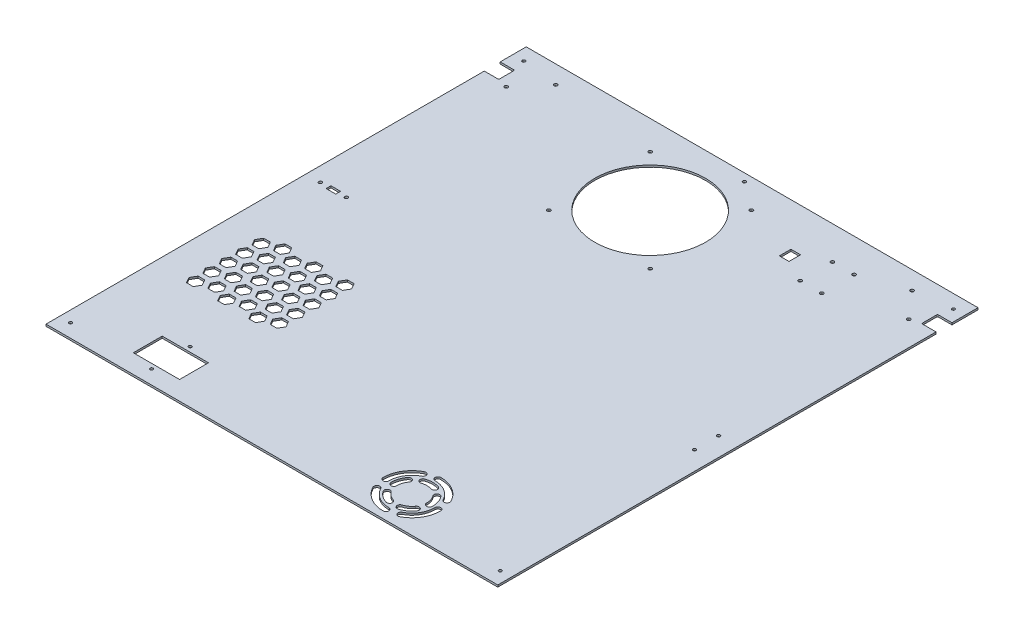
SolidWorks part; units mm, degrees
ref_plane "Alzado" through (0, 0, 0) normal (0, 0, 1) x (1, 0, 0)
ref_plane "Planta" through (0, 0, 0) normal (0, 1, 0) x (1, 0, 0)
ref_plane "Vista lateral" through (0, 0, 0) normal (1, 0, 0) x (0, 0, -1)
sketch "Croquis1" plane through (0, 0, 0) normal (0, 1, 0) x (1, 0, 0)
  line L1 (0, 0) -> (470.5, 0)
  line L2 (0, 0) -> (0, 420)
  line L3 (0, 420) -> (470.5, 420)
  line L4 (470.5, 0) -> (470.5, 420)
  dimension "D1" = 420
  dimension "D2" = 470.5
extrude "Saliente-Extruir1" add sketch "Croquis1" along normal blind 2
sketch "Croquis2" plane through (0, 2, 0) normal (0, 1, 0) x (1, 0, 0)
  line L0 (470.5, 420) -> (0, 420) construction
  line L1 (0, 420) -> (0, 0) construction
  line L2 (235.25, 420) -> (235.25, 0) construction
  line L3 (0, 0) -> (470.5, 0) construction
  line L4 (0, 210) -> (470.5, 210) construction
  line L5 (470.5, 0) -> (470.5, 420) construction
  circle A0 centre (12.5, 405) radius 1.55
  circle A1 centre (458, 405) radius 1.55
  circle A2 centre (458, 15) radius 1.55
  circle A3 centre (12.5, 15) radius 1.55
  dimension "D1" = 3.1
  dimension "D2" = 15
  dimension "D3" = 12.5
extrude "Cortar-Extruir1" cut sketch "Croquis2" against normal up to surface (2 mm away) up to face at (235.25, 0, -210)
sketch "Croquis3" plane through (0, 2, 0) normal (0, 1, 0) x (1, 0, 0)
  line L0 (470, 419.5) -> (0.5, 419.5)
  line L1 (0.5, 419.5) -> (0.5, 0.5)
  line L2 (0.5, 0.5) -> (470, 0.5)
  line L3 (470, 0.5) -> (470, 419.5)
  line L4 (0, 420) -> (0, 0)
  line L5 (0, 0) -> (470.5, 0)
  line L6 (470.5, 0) -> (470.5, 420)
  line L7 (470.5, 420) -> (0, 420)
  line L8 (0, 420) -> (0, 0)
  line L9 (0, 0) -> (470.5, 0)
  line L10 (470.5, 0) -> (470.5, 420)
  line L11 (470.5, 420) -> (0, 420)
  dimension "D1" = 0
  dimension "D2" = 0.5
extrude "Cortar-Extruir2" cut sketch "Croquis3" against normal up to surface (2 mm away) up to face at (12.5, 0, -16.55)
sketch "Croquis4" plane through (0, 2, 0) normal (0, 1, 0) x (1, 0, 0)
  line L0 (0.5, 0.5) -> (470, 0.5) construction
  line L1 (0.5, 419.5) -> (0.5, 0.5) construction
  circle A0 centre (343.5, 38) radius 27 construction
  arc A1 (343.5, 65) -> (367.4419, 50.4815) centre (343.5, 38) cw construction
  arc A2 (370.1021, 51.8683) -> (343.5, 68) centre (343.5, 38) ccw
  arc A3 (364.7817, 49.0947) -> (343.5, 62) centre (343.5, 38) ccw
  arc A4 (364.7817, 49.0947) -> (370.1021, 51.8683) centre (367.4419, 50.4815) ccw
  arc A5 (343.5, 68) -> (343.5, 62) centre (343.5, 65) ccw
  arc A6 (354.5947, 16.7183) -> (367.5, 38) centre (343.5, 38) ccw
  arc A7 (354.5947, 16.7183) -> (357.3683, 11.3979) centre (355.9815, 14.0581) ccw
  arc A8 (373.5, 38) -> (367.5, 38) centre (370.5, 38) ccw
  arc A9 (357.3683, 11.3979) -> (373.5, 38) centre (343.5, 38) ccw
  arc A10 (370.5, 38) -> (355.9815, 14.0581) centre (343.5, 38) cw construction
  arc A11 (322.2183, 26.9053) -> (343.5, 14) centre (343.5, 38) ccw
  arc A12 (322.2183, 26.9053) -> (316.8979, 24.1317) centre (319.5581, 25.5185) ccw
  arc A13 (343.5, 8) -> (343.5, 14) centre (343.5, 11) ccw
  arc A14 (316.8979, 24.1317) -> (343.5, 8) centre (343.5, 38) ccw
  arc A15 (343.5, 11) -> (319.5581, 25.5185) centre (343.5, 38) cw construction
  arc A16 (332.4053, 59.2817) -> (319.5, 38) centre (343.5, 38) ccw
  arc A17 (332.4053, 59.2817) -> (329.6317, 64.6021) centre (331.0185, 61.9419) ccw
  arc A18 (313.5, 38) -> (319.5, 38) centre (316.5, 38) ccw
  arc A19 (329.6317, 64.6021) -> (313.5, 38) centre (343.5, 38) ccw
  arc A20 (316.5, 38) -> (331.0185, 61.9419) centre (343.5, 38) cw construction
  circle A21 centre (343.5, 38) radius 18.5 construction
  arc A22 (337.5, 55.5) -> (349.5, 55.5) centre (343.5, 38) cw construction
  arc A23 (350.473, 58.3378) -> (336.527, 58.3378) centre (343.5, 38) ccw
  arc A24 (348.527, 52.6622) -> (338.473, 52.6622) centre (343.5, 38) ccw
  arc A25 (348.527, 52.6622) -> (350.473, 58.3378) centre (349.5, 55.5) ccw
  arc A26 (336.527, 58.3378) -> (338.473, 52.6622) centre (337.5, 55.5) ccw
  arc A27 (358.2894, 49.1141) -> (361.9976, 37.7015) centre (343.5, 38) cw construction
  arc A28 (364.9972, 37.653) -> (360.6877, 50.9164) centre (343.5, 38) ccw
  arc A29 (358.998, 37.7499) -> (355.8911, 47.3118) centre (343.5, 38) ccw
  arc A30 (358.998, 37.7499) -> (364.9972, 37.653) centre (361.9976, 37.7015) ccw
  arc A31 (360.6877, 50.9164) -> (355.8911, 47.3118) centre (358.2894, 49.1141) ccw
  arc A32 (358.6403, 27.3689) -> (348.9321, 20.3155) centre (343.5, 38) cw construction
  arc A33 (349.813, 17.4477) -> (361.0955, 25.645) centre (343.5, 38) ccw
  arc A34 (348.0513, 23.1832) -> (356.1852, 29.0929) centre (343.5, 38) ccw
  arc A35 (348.0513, 23.1832) -> (349.813, 17.4477) centre (348.9321, 20.3155) ccw
  arc A36 (361.0955, 25.645) -> (356.1852, 29.0929) centre (358.6403, 27.3689) ccw
  arc A37 (338.0679, 20.3155) -> (328.3597, 27.3689) centre (343.5, 38) cw construction
  arc A38 (325.9045, 25.645) -> (337.187, 17.4477) centre (343.5, 38) ccw
  arc A39 (330.8148, 29.0929) -> (338.9487, 23.1832) centre (343.5, 38) ccw
  arc A40 (330.8148, 29.0929) -> (325.9045, 25.645) centre (328.3597, 27.3689) ccw
  arc A41 (337.187, 17.4477) -> (338.9487, 23.1832) centre (338.0679, 20.3155) ccw
  arc A42 (325.0024, 37.7015) -> (328.7106, 49.1141) centre (343.5, 38) cw construction
  arc A43 (326.3123, 50.9164) -> (322.0028, 37.653) centre (343.5, 38) ccw
  arc A44 (331.1089, 47.3118) -> (328.002, 37.7499) centre (343.5, 38) ccw
  arc A45 (331.1089, 47.3118) -> (326.3123, 50.9164) centre (328.7106, 49.1141) ccw
  arc A46 (322.0028, 37.653) -> (328.002, 37.7499) centre (325.0024, 37.7015) ccw
  circle A94 centre (458, 405) radius 1.55 construction
  point P9 (357.5, 61.0868)
  point P19 (366.5868, 24)
  point P26 (329.5, 14.9132)
  point P33 (320.4132, 52)
  point P38 (343.5, 38)
  point P40 (343.5, 56.5)
  point P48 (361.0945, 43.7168)
  point P57 (354.374, 23.0332)
  point P64 (332.626, 23.0332)
  point P71 (325.9055, 43.7168)
  point P76 (343.5, 38)
  point P125 (302, 221.5)
  point P183 (302, 221.5)
  dimension "D1" = 54
  dimension "D7" = 37
  dimension "D2" = 37.5
  dimension "D3" = 343
  dimension "D4" = 28
  dimension "D5" = 6
  dimension "D8" = 12
  dimension "D9" = 6
  dimension "D6" = 4
  dimension "D10" = 5
extrude "Cortar-Extruir3" cut sketch "Croquis4" against normal up to surface (2 mm away) up to face at (12.5, 0, -406.55)
sketch "Croquis5" plane through (0, 0, 0) normal (0, -1, 0) x (1, 0, 0)
  line L0 (120, -35.5) -> (72, -35.5) construction
  line L1 (120, -50.5) -> (72, -50.5)
  line L2 (120, -50.5) -> (120, -20.5)
  line L3 (120, -20.5) -> (72, -20.5)
  line L4 (72, -50.5) -> (72, -20.5)
  line L5 (470, -0.5) -> (470, -419.5) construction
  line L6 (0.5, -0.5) -> (470, -0.5) construction
  circle A1 centre (96, -15.5) radius 1.55
  circle A2 centre (96, -55.5) radius 1.55
  dimension "D3" = 3.1
  dimension "D1" = 48
  dimension "D2" = 30
  dimension "D4" = 5
  dimension "D5" = 24
  dimension "D6" = 350
  dimension "D7" = 20
extrude "Cortar-Extruir4" cut sketch "Croquis5" against normal up to surface (2 mm away) up to face at (343.5, 2, -55.5135)
sketch "Croquis8" plane through (0, 0, 0) normal (0, -1, 0) x (1, 0, 0)
  line L1 (470, -419.5) -> (0.5, -419.5)
  line L2 (470, -419.5) -> (470, -449.5)
  line L3 (470, -449.5) -> (0.5, -449.5)
  line L4 (0.5, -419.5) -> (0.5, -449.5)
  dimension "D1" = 30
extrude "Saliente-Extruir2" add sketch "Croquis8" against normal up to surface (2 mm away) up to face at (96, 2, -57.05)
sketch "Croquis10" plane through (0, 0, 0) normal (0, -1, 0) x (1, 0, 0)
  circle A0 centre (458, -405) radius 1.75
  circle A1 centre (12.5, -405) radius 1.75
  dimension "D1" = 3.5
  dimension "D2" = 3.5
extrude "Saliente-Extruir3" add sketch "Croquis10" against normal up to surface (2 mm away) up to face at (96, 2, -57.05)
sketch "Croquis11" plane through (0, 0, -449.5) normal (0, 0, -1) x (-1, 0, 0)
  line L4 (-0.5, 2) -> (-470, 2)
  line L5 (-470, 2) -> (-470, 0)
  line L6 (-470, 0) -> (-0.5, 0)
  line L7 (-0.5, 0) -> (-0.5, 2)
  line L8 (-0.5, 2) -> (-470, 2)
  line L9 (-470, 2) -> (-470, 0)
  line L10 (-470, 0) -> (-0.5, 0)
  line L11 (-0.5, 0) -> (-0.5, 2)
  dimension "D1" = 0
extrude "Saliente-Extruir4" add sketch "Croquis11" along normal blind 50
sketch "Croquis12" plane through (0, 0, 0) normal (0, -1, 0) x (1, 0, 0)
  line L0 (470, -0.5) -> (470, -499.5) construction
  line L1 (0.5, -499.5) -> (0.5, -0.5) construction
  line L3 (470, -499.5) -> (0.5, -499.5) construction
  circle A0 centre (458, -485) radius 1.55
  circle A1 centre (12.5, -485) radius 1.55
  dimension "D1" = 3.1
  dimension "D2" = 3.1
  dimension "D3" = 12
  dimension "D4" = 12
  dimension "D5" = 14.5
  dimension "D6" = 14.5
extrude "Cortar-Extruir8" cut sketch "Croquis12" against normal up to surface (2 mm away) up to face at (96, 2, -57.05)
sketch "Croquis13" plane through (0, 0, 0) normal (0, -1, 0) x (1, 0, 0)
  line L0 (470, -0.5) -> (470, -499.5) construction
  line L1 (470, -499.5) -> (0.5, -499.5) construction
  line L3 (330, -454.5) -> (320, -454.5)
  line L4 (330, -454.5) -> (330, -442.5)
  line L5 (330, -442.5) -> (320, -442.5)
  line L6 (320, -454.5) -> (320, -442.5)
  circle A0 centre (353, -464.5) radius 1.75
  circle A1 centre (353, -431) radius 1.75
  circle A2 centre (375.5, -464.5) radius 1.75
  circle A3 centre (375.5, -431) radius 1.75
  dimension "D1" = 3.5
  dimension "D2" = 33.5
  dimension "D3" = 117
  dimension "D4" = 35
  dimension "D5" = 10
  dimension "D6" = 12
  dimension "D7" = 45
  dimension "D8" = 150
  dimension "D9" = 22.5
  dimension "D10" = 22.5
extrude "Cortar-Extruir9" cut sketch "Croquis13" against normal up to surface (2 mm away) up to face at (458, 2, -486.55)
sketch "Croquis15" plane through (0, 0, 0) normal (0, -1, 0) x (1, 0, 0)
  line L0 (470, -0.5) -> (470, -499.5) construction
  line L2 (470, -499.5) -> (0.5, -499.5) construction
  circle A0 centre (450, -249.5) radius 1.6
  circle A1 centre (450, -224.5) radius 1.6
  dimension "D1" = 3.2
  dimension "D2" = 25
  dimension "D3" = 20
  dimension "D4" = 250
extrude "Cortar-Extruir11" cut sketch "Croquis15" against normal up to surface (2 mm away) up to face at (353, 2, -432.75)
sketch "Croquis16" plane through (0, 0, 0) normal (0, -1, 0) x (1, 0, 0)
  line L4 (0.5, -0.5) -> (470, -0.5) construction
  line L5 (0.5, -499.5) -> (0.5, -0.5) construction
  line L6 (470, -0.5) -> (470, -499.5) construction
  line L7 (470, -499.5) -> (0.5, -499.5) construction
  line L8 (1, -1) -> (1, -499)
  line L9 (1, -499) -> (469.5, -499)
  line L10 (469.5, -499) -> (469.5, -1)
  line L11 (469.5, -1) -> (1, -1)
  line L12 (1, -1) -> (1, -499)
  line L13 (1, -499) -> (469.5, -499)
  line L14 (469.5, -499) -> (469.5, -1)
  line L15 (469.5, -1) -> (1, -1)
  line L16 (0.5, -0.5) -> (470, -0.5)
  line L17 (0.5, -499.5) -> (0.5, -0.5)
  line L18 (470, -0.5) -> (470, -499.5)
  line L19 (470, -499.5) -> (0.5, -499.5)
  dimension "D1" = 0.5
extrude "Cortar-Extruir12" cut sketch "Croquis16" against normal up to surface (2 mm away) up to face at (450, 2, -251.1)
sketch "Croquis17" plane through (0, 2, 0) normal (0, 1, 0) x (1, 0, 0)
  line L0 (469.5, 499) -> (1, 499) construction
  line L1 (1, 499) -> (1, 1) construction
  circle A0 centre (235.25, 491) radius 1.6
  dimension "D1" = 3.2
  dimension "D2" = 8
  dimension "D3" = 234.25
extrude "Cortar-Extruir13" cut sketch "Croquis17" against normal up to surface (2 mm away) up to face at (12.5, 0, -16.55)
sketch "Croquis18" plane through (0, 0, 0) normal (0, -1, 0) x (1, 0, 0)
  line L0 (34.5, -270.5) -> (16, -270.5) construction
  line L1 (34.5, -273) -> (24.5, -273)
  line L2 (34.5, -273) -> (34.5, -268)
  line L3 (34.5, -268) -> (24.5, -268)
  line L4 (24.5, -273) -> (24.5, -268)
  line L5 (34.5, -270.5) -> (43, -270.5) construction
  line L6 (29.5, -273) -> (29.5, -268) construction
  line L7 (1, -1) -> (1, -499) construction
  line L9 (72, -50.5) -> (120, -50.5) construction
  circle A0 centre (16, -270.5) radius 1.65
  circle A1 centre (43, -270.5) radius 1.65
  dimension "D3" = 3.3
  dimension "D4" = 3.3
  dimension "D1" = 10
  dimension "D2" = 5
  dimension "D5" = 27
  dimension "D6" = 13.5
  dimension "D7" = 15
  dimension "D8" = 220
extrude "Cortar-Extruir14" cut sketch "Croquis18" against normal up to surface (2 mm away) up to face at (235.25, 2, -489.4)
sketch "Croquis19" plane through (0, 0, 0) normal (0, -1, 0) x (1, 0, 0)
  line L0 (1, -1) -> (1, -499) construction
  line L1 (114.0718, -191) -> (117.5359, -197)
  line L2 (117.5359, -197) -> (124.4641, -197)
  line L3 (124.4641, -197) -> (127.9282, -191)
  line L4 (127.9282, -191) -> (124.4641, -185)
  line L5 (124.4641, -185) -> (117.5359, -185)
  line L6 (117.5359, -185) -> (114.0718, -191)
  line L7 (469.5, -1) -> (1, -1) construction
  line L176 (114.0718, -174) -> (117.5359, -180)
  line L177 (97.906, -185) -> (101.3701, -191)
  line L178 (101.3701, -191) -> (108.2983, -191)
  line L179 (108.2983, -191) -> (111.7624, -185)
  line L180 (111.7624, -185) -> (108.2983, -179)
  line L181 (108.2983, -179) -> (101.3701, -179)
  line L182 (101.3701, -179) -> (97.906, -185)
  line L183 (117.5359, -180) -> (124.4641, -180)
  line L184 (124.4641, -180) -> (127.9282, -174)
  line L185 (127.9282, -174) -> (124.4641, -168)
  line L186 (124.4641, -168) -> (117.5359, -168)
  line L187 (117.5359, -168) -> (114.0718, -174)
  line L188 (97.906, -168) -> (101.3701, -174)
  line L189 (101.3701, -174) -> (108.2983, -174)
  line L190 (108.2983, -174) -> (111.7624, -168)
  line L191 (111.7624, -168) -> (108.2983, -162)
  line L192 (108.2983, -162) -> (101.3701, -162)
  line L193 (101.3701, -162) -> (97.906, -168)
  line L194 (114.0718, -157) -> (117.5359, -163)
  line L195 (117.5359, -163) -> (124.4641, -163)
  line L196 (124.4641, -163) -> (127.9282, -157)
  line L197 (127.9282, -157) -> (124.4641, -151)
  line L198 (124.4641, -151) -> (117.5359, -151)
  line L199 (117.5359, -151) -> (114.0718, -157)
  line L200 (97.906, -151) -> (101.3701, -157)
  line L201 (101.3701, -157) -> (108.2983, -157)
  line L202 (108.2983, -157) -> (111.7624, -151)
  line L203 (111.7624, -151) -> (108.2983, -145)
  line L204 (108.2983, -145) -> (101.3701, -145)
  line L205 (101.3701, -145) -> (97.906, -151)
  line L206 (114.0718, -140) -> (117.5359, -146)
  line L207 (117.5359, -146) -> (124.4641, -146)
  line L208 (124.4641, -146) -> (127.9282, -140)
  line L209 (127.9282, -140) -> (124.4641, -134)
  line L210 (124.4641, -134) -> (117.5359, -134)
  line L211 (117.5359, -134) -> (114.0718, -140)
  line L212 (97.906, -134) -> (101.3701, -140)
  line L213 (101.3701, -140) -> (108.2983, -140)
  line L214 (108.2983, -140) -> (111.7624, -134)
  line L215 (111.7624, -134) -> (108.2983, -128)
  line L216 (108.2983, -128) -> (101.3701, -128)
  line L217 (101.3701, -128) -> (97.906, -134)
  line L218 (114.0718, -123) -> (117.5359, -129)
  line L219 (117.5359, -129) -> (124.4641, -129)
  line L220 (124.4641, -129) -> (127.9282, -123)
  line L221 (127.9282, -123) -> (124.4641, -117)
  line L222 (124.4641, -117) -> (117.5359, -117)
  line L223 (117.5359, -117) -> (114.0718, -123)
  line L224 (97.906, -117) -> (101.3701, -123)
  line L225 (101.3701, -123) -> (108.2983, -123)
  line L226 (108.2983, -123) -> (111.7624, -117)
  line L227 (111.7624, -117) -> (108.2983, -111)
  line L228 (108.2983, -111) -> (101.3701, -111)
  line L229 (101.3701, -111) -> (97.906, -117)
  line L230 (81.7402, -191) -> (85.2043, -197)
  line L231 (85.2043, -197) -> (92.1325, -197)
  line L232 (92.1325, -197) -> (95.5966, -191)
  line L233 (95.5966, -191) -> (92.1325, -185)
  line L234 (92.1325, -185) -> (85.2043, -185)
  line L235 (85.2043, -185) -> (81.7402, -191)
  line L236 (81.7402, -174) -> (85.2043, -180)
  line L237 (65.5744, -185) -> (69.0385, -191)
  line L238 (69.0385, -191) -> (75.9667, -191)
  line L239 (75.9667, -191) -> (79.4308, -185)
  line L240 (79.4308, -185) -> (75.9667, -179)
  line L241 (75.9667, -179) -> (69.0385, -179)
  line L242 (69.0385, -179) -> (65.5744, -185)
  line L243 (85.2043, -180) -> (92.1325, -180)
  line L244 (92.1325, -180) -> (95.5966, -174)
  line L245 (95.5966, -174) -> (92.1325, -168)
  line L246 (92.1325, -168) -> (85.2043, -168)
  line L247 (85.2043, -168) -> (81.7402, -174)
  line L248 (65.5744, -168) -> (69.0385, -174)
  line L249 (69.0385, -174) -> (75.9667, -174)
  line L250 (75.9667, -174) -> (79.4308, -168)
  line L251 (79.4308, -168) -> (75.9667, -162)
  line L252 (75.9667, -162) -> (69.0385, -162)
  line L253 (69.0385, -162) -> (65.5744, -168)
  line L254 (81.7402, -157) -> (85.2043, -163)
  line L255 (85.2043, -163) -> (92.1325, -163)
  line L256 (92.1325, -163) -> (95.5966, -157)
  line L257 (95.5966, -157) -> (92.1325, -151)
  line L258 (92.1325, -151) -> (85.2043, -151)
  line L259 (85.2043, -151) -> (81.7402, -157)
  line L260 (65.5744, -151) -> (69.0385, -157)
  line L261 (69.0385, -157) -> (75.9667, -157)
  line L262 (75.9667, -157) -> (79.4308, -151)
  line L263 (79.4308, -151) -> (75.9667, -145)
  line L264 (75.9667, -145) -> (69.0385, -145)
  line L265 (69.0385, -145) -> (65.5744, -151)
  line L266 (81.7402, -140) -> (85.2043, -146)
  line L267 (85.2043, -146) -> (92.1325, -146)
  line L268 (92.1325, -146) -> (95.5966, -140)
  line L269 (95.5966, -140) -> (92.1325, -134)
  line L270 (92.1325, -134) -> (85.2043, -134)
  line L271 (85.2043, -134) -> (81.7402, -140)
  line L272 (65.5744, -134) -> (69.0385, -140)
  line L273 (69.0385, -140) -> (75.9667, -140)
  line L274 (75.9667, -140) -> (79.4308, -134)
  line L275 (79.4308, -134) -> (75.9667, -128)
  line L276 (75.9667, -128) -> (69.0385, -128)
  line L277 (69.0385, -128) -> (65.5744, -134)
  line L278 (81.7402, -123) -> (85.2043, -129)
  line L279 (85.2043, -129) -> (92.1325, -129)
  line L280 (92.1325, -129) -> (95.5966, -123)
  line L281 (95.5966, -123) -> (92.1325, -117)
  line L282 (92.1325, -117) -> (85.2043, -117)
  line L283 (85.2043, -117) -> (81.7402, -123)
  line L284 (65.5744, -117) -> (69.0385, -123)
  line L285 (69.0385, -123) -> (75.9667, -123)
  line L286 (75.9667, -123) -> (79.4308, -117)
  line L287 (79.4308, -117) -> (75.9667, -111)
  line L288 (75.9667, -111) -> (69.0385, -111)
  line L289 (69.0385, -111) -> (65.5744, -117)
  line L290 (49.4086, -191) -> (52.8727, -197)
  line L291 (52.8727, -197) -> (59.8009, -197)
  line L292 (59.8009, -197) -> (63.265, -191)
  line L293 (63.265, -191) -> (59.8009, -185)
  line L294 (59.8009, -185) -> (52.8727, -185)
  line L295 (52.8727, -185) -> (49.4086, -191)
  line L296 (49.4086, -174) -> (52.8727, -180)
  line L297 (33.2428, -185) -> (36.7069, -191)
  line L298 (36.7069, -191) -> (43.6351, -191)
  line L299 (43.6351, -191) -> (47.0992, -185)
  line L300 (47.0992, -185) -> (43.6351, -179)
  line L301 (43.6351, -179) -> (36.7069, -179)
  line L302 (36.7069, -179) -> (33.2428, -185)
  line L303 (52.8727, -180) -> (59.8009, -180)
  line L304 (59.8009, -180) -> (63.265, -174)
  line L305 (63.265, -174) -> (59.8009, -168)
  line L306 (59.8009, -168) -> (52.8727, -168)
  line L307 (52.8727, -168) -> (49.4086, -174)
  line L308 (33.2428, -168) -> (36.7069, -174)
  line L309 (36.7069, -174) -> (43.6351, -174)
  line L310 (43.6351, -174) -> (47.0992, -168)
  line L311 (47.0992, -168) -> (43.6351, -162)
  line L312 (43.6351, -162) -> (36.7069, -162)
  line L313 (36.7069, -162) -> (33.2428, -168)
  line L314 (49.4086, -157) -> (52.8727, -163)
  line L315 (52.8727, -163) -> (59.8009, -163)
  line L316 (59.8009, -163) -> (63.265, -157)
  line L317 (63.265, -157) -> (59.8009, -151)
  line L318 (59.8009, -151) -> (52.8727, -151)
  line L319 (52.8727, -151) -> (49.4086, -157)
  line L320 (33.2428, -151) -> (36.7069, -157)
  line L321 (36.7069, -157) -> (43.6351, -157)
  line L322 (43.6351, -157) -> (47.0992, -151)
  line L323 (47.0992, -151) -> (43.6351, -145)
  line L324 (43.6351, -145) -> (36.7069, -145)
  line L325 (36.7069, -145) -> (33.2428, -151)
  line L326 (49.4086, -140) -> (52.8727, -146)
  line L327 (52.8727, -146) -> (59.8009, -146)
  line L328 (59.8009, -146) -> (63.265, -140)
  line L329 (63.265, -140) -> (59.8009, -134)
  line L330 (59.8009, -134) -> (52.8727, -134)
  line L331 (52.8727, -134) -> (49.4086, -140)
  line L332 (33.2428, -134) -> (36.7069, -140)
  line L333 (36.7069, -140) -> (43.6351, -140)
  line L334 (43.6351, -140) -> (47.0992, -134)
  line L335 (47.0992, -134) -> (43.6351, -128)
  line L336 (43.6351, -128) -> (36.7069, -128)
  line L337 (36.7069, -128) -> (33.2428, -134)
  line L338 (49.4086, -123) -> (52.8727, -129)
  line L339 (52.8727, -129) -> (59.8009, -129)
  line L340 (59.8009, -129) -> (63.265, -123)
  line L341 (63.265, -123) -> (59.8009, -117)
  line L342 (59.8009, -117) -> (52.8727, -117)
  line L343 (52.8727, -117) -> (49.4086, -123)
  line L344 (33.2428, -117) -> (36.7069, -123)
  line L345 (36.7069, -123) -> (43.6351, -123)
  line L346 (43.6351, -123) -> (47.0992, -117)
  line L347 (47.0992, -117) -> (43.6351, -111)
  line L348 (43.6351, -111) -> (36.7069, -111)
  line L349 (36.7069, -111) -> (33.2428, -117)
  circle A0 centre (121, -191) radius 6 construction
  circle A1 centre (104.8342, -185) radius 6 construction
  dimension "D1" = 12
  dimension "D2" = 190
  dimension "D3" = 120
  dimension "D6" = 5
  dimension "D7" = 5
  dimension "D4" = 5
  dimension "D5" = 12
  dimension "D9" = 5
  dimension "D8" = 3
extrude "Cortar-Extruir15" cut sketch "Croquis19" against normal up to surface (2 mm away) up to face at (43, 2, -272.15)
sketch "Croquis20" plane through (0, 0, 0) normal (0, -1, 0) x (1, 0, 0)
  line L0 (1, -499) -> (469.5, -499) construction
  line L1 (264.5, -469) -> (159.5, -469) construction
  line L2 (264.5, -469) -> (264.5, -364) construction
  line L3 (264.5, -364) -> (159.5, -364) construction
  line L4 (159.5, -469) -> (159.5, -364) construction
  line L5 (469.5, -499) -> (469.5, -1) construction
  line L6 (159.5, -469) -> (264.5, -364) construction
  circle A0 centre (264.5, -469) radius 1.75
  circle A1 centre (159.5, -469) radius 1.75
  circle A2 centre (159.5, -364) radius 1.75
  circle A3 centre (264.5, -364) radius 1.75
  circle A4 centre (212, -416.5) radius 57.5
  dimension "D5" = 3.5
  dimension "D6" = 115
  dimension "D1" = 105
  dimension "D2" = 105
  dimension "D3" = 30
  dimension "D4" = 205
extrude "Cortar-Extruir16" cut sketch "Croquis20" against normal up to surface (2 mm away) up to face at (72.5026, 2, -168)
sketch "Croquis21" plane through (0, 0, 0) normal (0, -1, 0) x (1, 0, 0)
  line L0 (469.5, -499) -> (469.5, -1) construction
  line L1 (1, -499) -> (469.5, -499) construction
  line L2 (235.25, -1) -> (235.25, -499) construction
  line L4 (469.5, -1) -> (1, -1) construction
  circle A0 centre (444, -452.66) radius 1.75
  circle A1 centre (420, -480.16) radius 1.75
  circle A3 centre (26.5, -452.66) radius 1.75
  circle A4 centre (50.5, -480.16) radius 1.75
  dimension "D3" = 3.5
  dimension "D1" = 25.5
  dimension "D2" = 46.34
  dimension "D4" = 49.5
  dimension "D5" = 18.84
extrude "Cortar-Extruir17" cut sketch "Croquis21" against normal up to surface (2 mm away) up to face at (159.5, 2, -470.75)
sketch "Croquis22" plane through (0, 0, 0) normal (0, -1, 0) x (1, 0, 0)
  line L0 (469.5, -499) -> (469.5, -1) construction
  line L1 (469.5, -472) -> (454.5, -472)
  line L2 (469.5, -472) -> (469.5, -455.5)
  line L3 (469.5, -455.5) -> (454.5, -455.5)
  line L4 (454.5, -472) -> (454.5, -455.5)
  line L5 (1, -499) -> (469.5, -499) construction
  line L6 (235.25, -1) -> (235.25, -499) construction
  line L7 (469.5, -1) -> (1, -1) construction
  line L8 (16, -472) -> (16, -455.5)
  line L9 (1, -455.5) -> (16, -455.5)
  line L10 (1, -472) -> (1, -455.5)
  line L11 (1, -472) -> (16, -472)
  dimension "D1" = 15
  dimension "D2" = 16.5
  dimension "D3" = 27
extrude "Cortar-Extruir18" cut sketch "Croquis22" against normal up to surface (2 mm away) up to face at (444, 2, -454.41)
fillet "Redondeo1" radius 1 4 edges at (16, 1, -455.5) (16, 1, -472) (454.5, 1, -455.5) (454.5, 1, -472)
